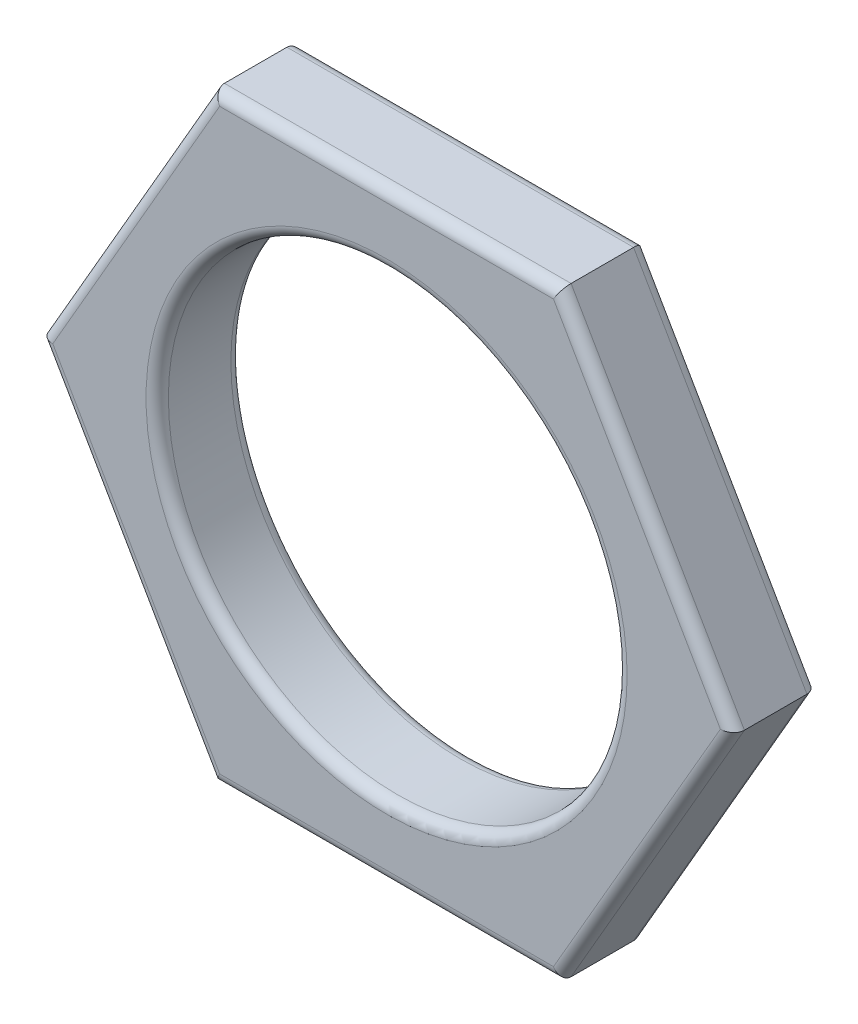
SolidWorks part; units mm, degrees
ref_plane "Piano frontale" through (0, 0, 0) normal (0, 0, 1) x (1, 0, 0)
ref_plane "Piano superiore" through (0, 0, 0) normal (0, 1, 0) x (1, 0, 0)
ref_plane "Piano destro" through (0, 0, 0) normal (1, 0, 0) x (0, 0, -1)
sketch "Schizzo1" plane through (0, 0, 0) normal (0, 0, 1) x (1, 0, 0)
  line L1 (-15.5307, 0) -> (-7.7654, -13.45)
  line L2 (-7.7654, -13.45) -> (7.7654, -13.45)
  line L3 (7.7654, -13.45) -> (15.5307, 0)
  line L4 (15.5307, 0) -> (7.7654, 13.45)
  line L5 (7.7654, 13.45) -> (-7.7654, 13.45)
  line L6 (-7.7654, 13.45) -> (-15.5307, 0)
  circle A0 centre (0, 0) radius 13.45 construction
  circle A1 centre (0, 0) radius 10.275
  dimension "D2" = 20.55
  dimension "D1" = 26.9
extrude "Estrusione-Estrusione1" add sketch "Schizzo1" along normal mid plane 3.8
fillet "Raccordo1" radius 0.5 14 edges at (10.275, 0, -1.9) (-11.648, -6.725, -1.9) (0, -13.45, -1.9) (11.648, -6.725, -1.9) (11.648, 6.725, -1.9) (0, 13.45, -1.9) (-11.648, 6.725, -1.9) (10.275, 0, 1.9) (0, 13.45, 1.9) (11.648, 6.725, 1.9) (11.648, -6.725, 1.9) (0, -13.45, 1.9) (-11.648, -6.725, 1.9) (-11.648, 6.725, 1.9)
move or copy body "Corpo-Sposta/copia1" [suppressed] bodies to move or copy 101
